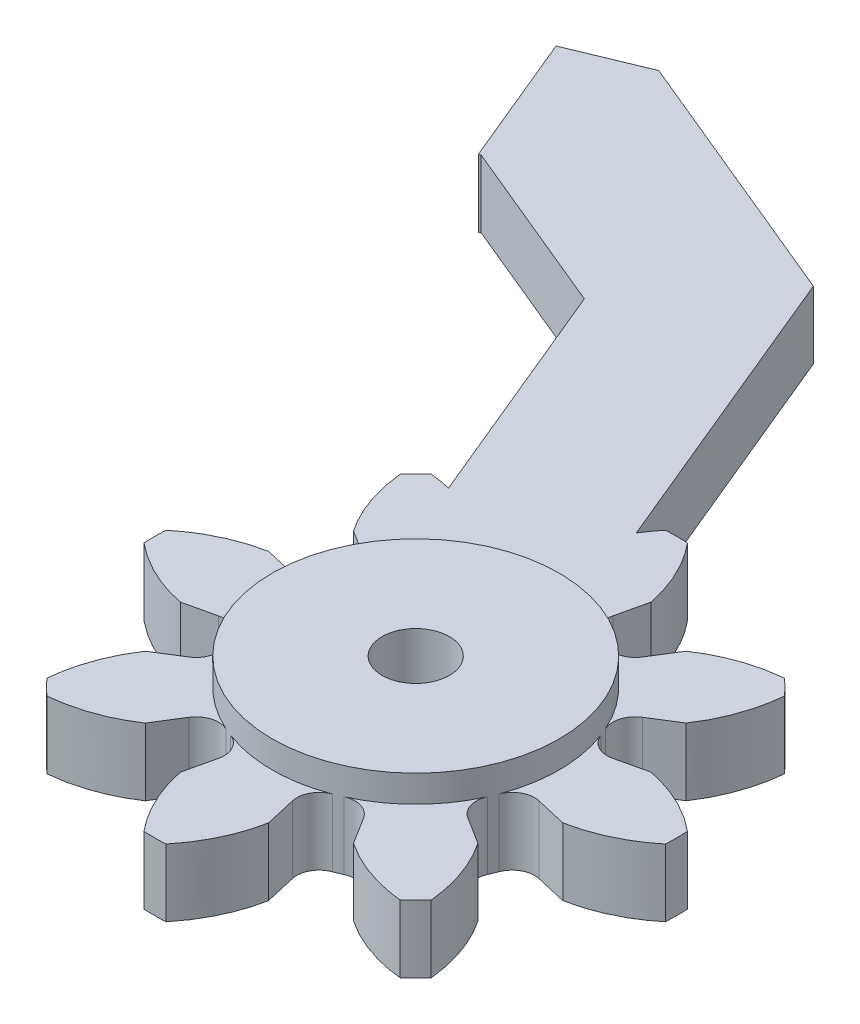
SolidWorks part; units mm, degrees
ref_plane "Front Plane" through (0, 0, 0) normal (0, 0, 1) x (1, 0, 0)
ref_plane "Top Plane" through (0, 0, 0) normal (0, 1, 0) x (1, 0, 0)
ref_plane "Right Plane" through (0, 0, 0) normal (1, 0, 0) x (0, 0, -1)
sketch "Sketch1" plane through (0, 0, 0) normal (0, 1, 0) x (1, 0, 0)
  circle A0 centre (0, 0) radius 6.3937
  dimension "D1" = 12.7875
extrude "Boss-Extrude1" add sketch "Sketch1" along normal blind 4.2
sketch "Sketch2" plane through (0, 0, 0) normal (0, 1, 0) x (1, 0, 0)
  line L0 (0, 0) -> (-1.9595, 8.5166) construction
  line L1 (0, 0) -> (5.1917, 7.0298) construction
  line L2 (0, 0) -> (8.7162, 0.6323) construction
  line L3 (0, 0) -> (6.1519, -6.207) construction
  line L4 (0, 0) -> (-0.71, -8.7103) construction
  line L5 (0, 0) -> (-7.0759, -5.1288) construction
  line L6 (-7.0759, -5.1288) -> (-0.71, -8.7103) construction
  line L7 (-0.71, -8.7103) -> (6.1519, -6.207) construction
  line L8 (6.1519, -6.207) -> (8.7162, 0.6323) construction
  line L9 (8.7162, 0.6323) -> (5.1917, 7.0298) construction
  line L10 (5.1917, 7.0298) -> (-1.9595, 8.5166) construction
  line L11 (5.1917, 7.0298) -> (-0.6838, 11.3691) construction
  line L12 (8.7162, 0.6323) -> (7.6594, 15.2024) construction
  line L13 (6.1519, -6.207) -> (21.7154, 9.2183) construction
  line L14 (-0.71, -8.7103) -> (28.4103, -11.0838) construction
  line L15 (-7.0759, -5.1288) -> (14.3576, -34.6989) construction
  line L16 (0, 0) -> (0, 11.625) construction
  line L17 (0, 0) -> (-1.8143, 9.1213) construction
  line L18 (-1.4336, 6.2309) -> (-1.9595, 8.5166)
  line L19 (1.4336, 6.2309) -> (1.9595, 8.5166)
  line L20 (3.3922, 5.4197) -> (4.6366, 7.4078)
  line L21 (5.4197, 3.3922) -> (7.4078, 4.6366)
  line L22 (6.2309, 1.4336) -> (8.5166, 1.9595)
  line L23 (6.2309, -1.4336) -> (8.5166, -1.9595)
  line L24 (5.4197, -3.3922) -> (7.4078, -4.6366)
  line L25 (3.3922, -5.4197) -> (4.6366, -7.4078)
  line L26 (1.4336, -6.2309) -> (1.9595, -8.5166)
  line L27 (-1.4336, -6.2309) -> (-1.9595, -8.5166)
  line L28 (-3.3922, -5.4197) -> (-4.6366, -7.4078)
  line L29 (-5.4197, -3.3922) -> (-7.4078, -4.6366)
  line L30 (-6.2309, -1.4336) -> (-8.5166, -1.9595)
  line L31 (-6.2309, 1.4336) -> (-8.5166, 1.9595)
  line L32 (-5.4197, 3.3922) -> (-7.4078, 4.6366)
  line L33 (-3.3922, 5.4197) -> (-4.6366, 7.4078)
  circle A0 centre (0, 0) radius 8.7392 construction
  circle A1 centre (0, 0) radius 9.3 construction
  circle A2 centre (0, 0) radius 11.625 construction
  circle A3 centre (0, 0) radius 6.3938 construction
  arc A4 (-0.489, 11.6147) -> (0.489, 11.6147) centre (0, 0) cw
  arc A6 (1.4336, 6.2309) -> (-1.4336, 6.2309) centre (0, 0) ccw
  arc A7 (7.8671, 8.5586) -> (8.5586, 7.8671) centre (0, 0) cw
  arc A8 (5.4197, 3.3922) -> (3.3922, 5.4197) centre (0, 0) ccw
  arc A9 (11.6147, 0.489) -> (11.6147, -0.489) centre (0, 0) cw
  arc A10 (6.2309, -1.4336) -> (6.2309, 1.4336) centre (0, 0) ccw
  arc A11 (8.5586, -7.8671) -> (7.8671, -8.5586) centre (0, 0) cw
  arc A12 (3.3922, -5.4197) -> (5.4197, -3.3922) centre (0, 0) ccw
  arc A13 (0.489, -11.6147) -> (-0.489, -11.6147) centre (0, 0) cw
  arc A14 (-1.4336, -6.2309) -> (1.4336, -6.2309) centre (0, 0) ccw
  arc A15 (-7.8671, -8.5586) -> (-8.5586, -7.8671) centre (0, 0) cw
  arc A16 (-5.4197, -3.3922) -> (-3.3922, -5.4197) centre (0, 0) ccw
  arc A17 (-11.6147, -0.489) -> (-11.6147, 0.489) centre (0, 0) cw
  arc A18 (-6.2309, 1.4336) -> (-6.2309, -1.4336) centre (0, 0) ccw
  arc A19 (-8.5586, 7.8671) -> (-7.8671, 8.5586) centre (0, 0) cw
  arc A20 (-3.3922, 5.4197) -> (-5.4197, 3.3922) centre (0, 0) ccw
  spline S0 degree 3 poles (-1.9595, 8.5166) (-1.1285, 12.8) (8.9048, 17.5947) (34.413, 4.764) (29.5229, -26.838) (14.3576, -34.6989) knots 0 0 0 0 0.160993 0.360844 1 1 1 1 construction
  spline S1 degree 3 poles (-1.9595, 8.5166) (-1.7453, 9.6444) (-1.2236, 10.7314) (-0.489, 11.6147) knots 0 0 0 0 1 1 1 1
  spline S2 degree 3 poles (1.9595, 8.5166) (1.7453, 9.6444) (1.2236, 10.7314) (0.489, 11.6147) knots 0 0 0 0 1 1 1 1
  spline S3 degree 3 poles (4.6366, 7.4078) (5.5855, 8.0537) (6.7231, 8.4535) (7.8671, 8.5586) knots 0 0 0 0 1 1 1 1
  spline S4 degree 3 poles (7.4078, 4.6366) (8.0537, 5.5855) (8.4535, 6.7231) (8.5586, 7.8671) knots 0 0 0 0 1 1 1 1
  spline S5 degree 3 poles (8.5166, 1.9595) (9.6444, 1.7453) (10.7314, 1.2236) (11.6147, 0.489) knots 0 0 0 0 1 1 1 1
  spline S6 degree 3 poles (8.5166, -1.9595) (9.6444, -1.7453) (10.7314, -1.2236) (11.6147, -0.489) knots 0 0 0 0 1 1 1 1
  spline S7 degree 3 poles (7.4078, -4.6366) (8.0537, -5.5855) (8.4535, -6.7231) (8.5586, -7.8671) knots 0 0 0 0 1 1 1 1
  spline S8 degree 3 poles (4.6366, -7.4078) (5.5855, -8.0537) (6.7231, -8.4535) (7.8671, -8.5586) knots 0 0 0 0 1 1 1 1
  spline S9 degree 3 poles (1.9595, -8.5166) (1.7453, -9.6444) (1.2236, -10.7314) (0.489, -11.6147) knots 0 0 0 0 1 1 1 1
  spline S10 degree 3 poles (-1.9595, -8.5166) (-1.7453, -9.6444) (-1.2236, -10.7314) (-0.489, -11.6147) knots 0 0 0 0 1 1 1 1
  spline S11 degree 3 poles (-4.6366, -7.4078) (-5.5855, -8.0537) (-6.7231, -8.4535) (-7.8671, -8.5586) knots 0 0 0 0 1 1 1 1
  spline S12 degree 3 poles (-7.4078, -4.6366) (-8.0537, -5.5855) (-8.4535, -6.7231) (-8.5586, -7.8671) knots 0 0 0 0 1 1 1 1
  spline S13 degree 3 poles (-8.5166, -1.9595) (-9.6444, -1.7453) (-10.7314, -1.2236) (-11.6147, -0.489) knots 0 0 0 0 1 1 1 1
  spline S14 degree 3 poles (-8.5166, 1.9595) (-9.6444, 1.7453) (-10.7314, 1.2236) (-11.6147, 0.489) knots 0 0 0 0 1 1 1 1
  spline S15 degree 3 poles (-7.4078, 4.6366) (-8.0537, 5.5855) (-8.4535, 6.7231) (-8.5586, 7.8671) knots 0 0 0 0 1 1 1 1
  spline S16 degree 3 poles (-4.6366, 7.4078) (-5.5855, 8.0537) (-6.7231, 8.4535) (-7.8671, 8.5586) knots 0 0 0 0 1 1 1 1
  dimension "D1" = 17.4783
  dimension "D2" = 18.6
  dimension "D3" = 23.25
  dimension "D4" = 7.3042
  dimension "D5" = 14.6084
  dimension "D6" = 21.9126
  dimension "D7" = 29.2168
  dimension "D8" = 36.521
  dimension "D9" = 11.25
  dimension "D10" = 8
extrude "Boss-Extrude2" add sketch "Sketch2" along normal blind 3
fillet "Fillet1" radius 1 16 edges at (-1.4336, 1.5, 6.2309) (1.4336, 1.5, 6.2309) (3.3922, 1.5, 5.4197) (-3.3922, 1.5, 5.4197) (-5.4197, 1.5, 3.3922) (-6.2309, 1.5, 1.4336) (6.2309, 1.5, 1.4336) (5.4197, 1.5, -3.3922) (5.4197, 1.5, 3.3922) (6.2309, 1.5, -1.4336) (1.4336, 1.5, -6.2309) (-5.4197, 1.5, -3.3922) (-1.4336, 1.5, -6.2309) (3.3922, 1.5, -5.4197) (-3.3922, 1.5, -5.4197) (-6.2309, 1.5, -1.4336)
sketch "Sketch3" plane through (0, 4.2, 0) normal (0, 1, 0) x (1, 0, 0)
  circle A0 centre (0, 0) radius 1.5
  dimension "D1" = 3
extrude "Cut-Extrude1" cut sketch "Sketch3" against normal through all
sketch "Sketch4" plane through (0, 0, 0) normal (0, -1, 0) x (1, 0, 0)
  line L0 (0, 0) -> (0, -11.625) construction
  line L1 (0, 0) -> (-4.607, -11.1222) construction
  line L2 (1.4257, -4.9201) -> (-4.4871, -2.4709)
  line L3 (-4.4871, -2.4709) -> (-13.5185, -24.2745)
  line L4 (-13.5185, -24.2745) -> (-19.1541, -21.9401)
  line L5 (-19.1541, -21.9401) -> (-21.6033, -27.8529)
  line L6 (-21.6033, -27.8529) -> (-10.0548, -32.6365)
  line L7 (-10.0548, -32.6365) -> (1.4257, -4.9201)
  arc A0 (-0.489, -11.6147) -> (0.489, -11.6147) centre (0, 0) ccw construction
  point P10 (-1.5307, -3.6955)
  dimension "D1" = 22.5
  dimension "D2" = 4
  dimension "D3" = 30
  dimension "D4" = 12.5
  dimension "D5" = 6.4
  dimension "D6" = 6.4
extrude "Boss-Extrude3" add sketch "Sketch4" against normal blind 3
chamfer "Chamfer1" distance 9 angle 45 1 edges at (-10.0548, 1.5, -32.6365)
chamfer "Chamfer2" distance 6 angle 45 1 edges at (-13.5185, 1.5, -24.2745)
equation "\"value\"= 7.3042"
equation "\"D4@Sketch2\"=\"value\""
equation "\"D5@Sketch2\"= 2*\"value\""
equation "\"D6@Sketch2\"=3*\"value\""
equation "\"D7@Sketch2\"=4*\"value\""
equation "\"D8@Sketch2\"=5*\"value\""
